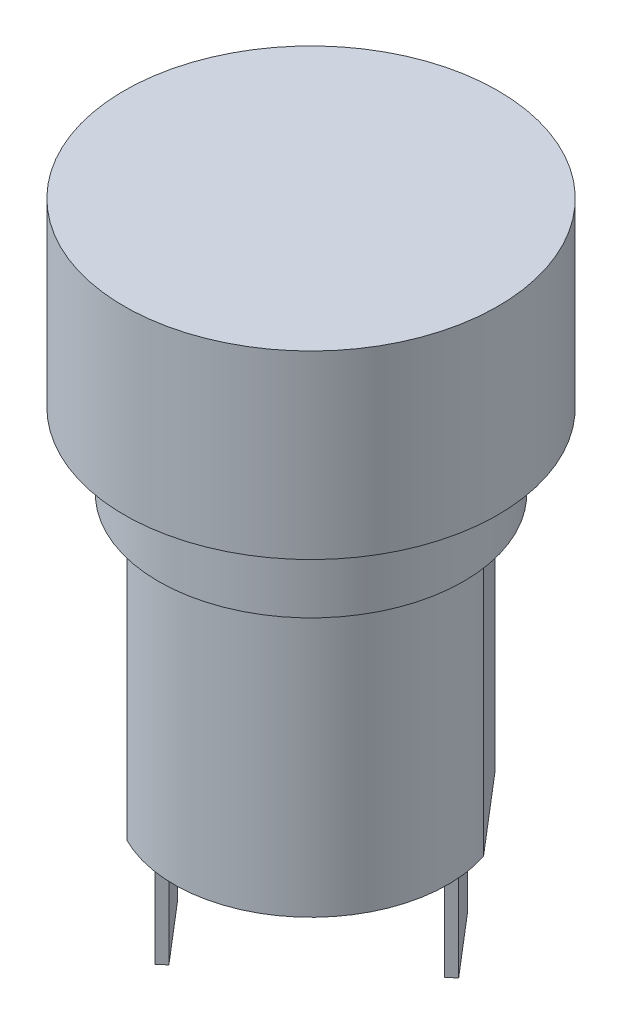
SolidWorks part; units mm, degrees
ref_plane "Front Plane" through (0, 0, 0) normal (0, 0, 1) x (1, 0, 0)
ref_plane "Top Plane" through (0, 0, 0) normal (0, 1, 0) x (1, 0, 0)
ref_plane "Right Plane" through (0, 0, 0) normal (1, 0, 0) x (0, 0, -1)
sketch "Sketch1" plane through (0, 0, 0) normal (0, 1, 0) x (1, 0, 0)
  circle A0 centre (0, 0) radius 11
  dimension "D1" = 22
extrude "Boss-Extrude1" add sketch "Sketch1" along normal blind 21.7 contours A0
sketch "Sketch7" plane through (0, 21.7, 0) normal (0, 1, 0) x (1, 0, 0)
  circle A0 centre (0, 0) radius 12.25
  dimension "D1" = 24.5
extrude "Boss-Extrude6" add sketch "Sketch7" along normal blind 6 contours A0
sketch "Sketch8" plane through (0, 27.7, 0) normal (0, 1, 0) x (1, 0, 0)
  circle A0 centre (0, 0) radius 15
  dimension "D1" = 30
extrude "Boss-Extrude7" add sketch "Sketch8" along normal blind 14.5
sketch "Sketch3" plane through (0, 0, 0) normal (0, -1, 0) x (1, 0, 0)
  line L4 (-4.9586, 9.819) -> (-10.4697, 3.3741)
  line L5 (10.4697, -3.3741) -> (4.9586, -9.819)
  circle A0 centre (0, 0) radius 11 construction
  arc A1 (-10.4697, 3.3741) -> (-4.9586, 9.819) centre (0, 0) cw
  arc A2 (4.9586, -9.819) -> (10.4697, -3.3741) centre (0, 0) ccw
  dimension "D1" = 20.3
extrude "Cut-Extrude4" cut sketch "Sketch3" against normal up to surface (21.7 mm away) up to face at (0, 21.7, 11)
sketch "Sketch9" plane through (0, 0, 0) normal (0, -1, 0) x (1, 0, 0)
  line L0 (8.0133, -2.7077) -> (3.9189, -7.4958)
  line L3 (8.6213, -3.2276) -> (4.5269, -8.0157)
  line L4 (4.5269, -8.0157) -> (3.9189, -7.4958)
  line L5 (3.9189, -7.4958) -> (8.0133, -2.7077)
  line L6 (8.0133, -2.7077) -> (8.6213, -3.2276)
  line L13 (10.4697, -3.3741) -> (4.9586, -9.819) construction
  line L15 (0, 0) -> (-0.6499, -0.76) construction
  line L16 (-3.9189, 7.4958) -> (-4.5269, 8.0157)
  line L17 (-8.0133, 2.7077) -> (-3.9189, 7.4958)
  line L18 (-8.6213, 3.2276) -> (-8.0133, 2.7077)
  line L19 (-4.5269, 8.0157) -> (-8.6213, 3.2276)
  line L20 (-3.9189, 7.4958) -> (-8.0133, 2.7077)
  dimension "D1" = 0.8
  dimension "D2" = 1
  dimension "D4" = 6.3
  dimension "D6" = 1.5
  dimension "D7" = 1.09
extrude "Boss-Extrude8" add sketch "Sketch9" along normal blind 9.3 contours L6 L0 L4 L3 | L16 L19 L18 L17
